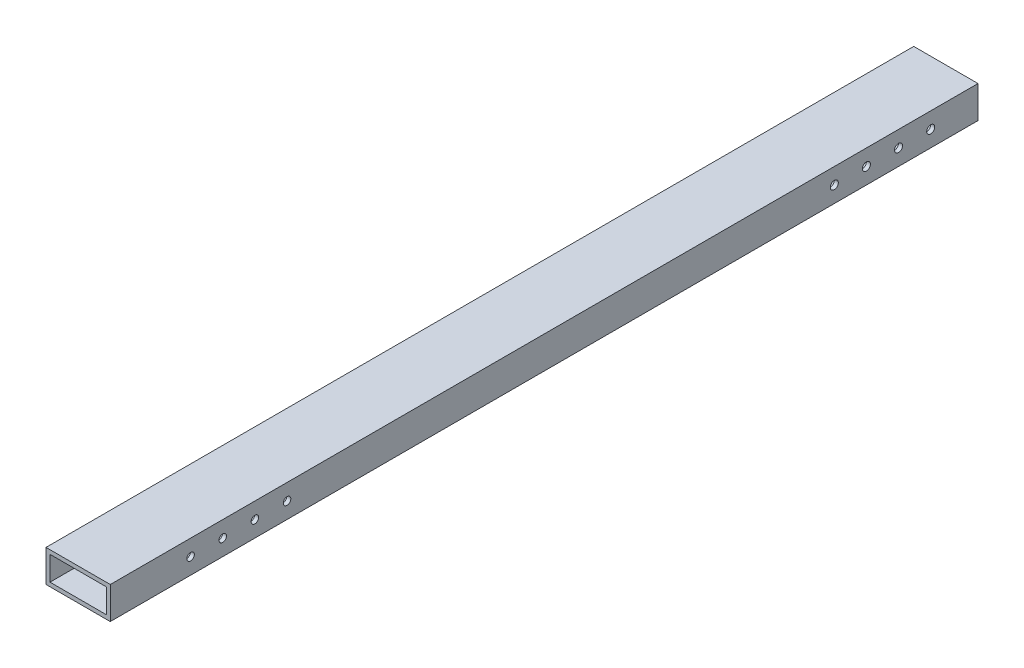
SolidWorks part; units mm, degrees
ref_plane "Front Plane" through (0, 0, 0) normal (0, 0, 1) x (1, 0, 0)
ref_plane "Top Plane" through (0, 0, 0) normal (0, 1, 0) x (1, 0, 0)
ref_plane "Right Plane" through (0, 0, 0) normal (1, 0, 0) x (0, 0, -1)
sketch "Sketch1" plane through (0, 0, 0) normal (0, 0, 1) x (1, 0, 0)
  line L0 (-22.225, 9.525) -> (22.225, 9.525)
  line L2 (-25.4, 12.7) -> (25.4, 12.7)
  line L3 (-25.4, 12.7) -> (-25.4, -12.7)
  line L4 (-25.4, -12.7) -> (25.4, -12.7)
  line L5 (25.4, 12.7) -> (25.4, -12.7)
  line L10 (22.225, 9.525) -> (22.225, -9.525)
  line L11 (-22.225, -9.525) -> (22.225, -9.525)
  line L12 (-22.225, 9.525) -> (-22.225, -9.525)
  point P12 (0, 12.7)
  point P14 (25.4, 0)
  dimension "Wall Thickness" = 3.175
  dimension "Outside Width" = 50.8
  dimension "Outside Height" = 25.4
  dimension "Inside Height" = 19.05
  dimension "Inside Width" = 44.45
sketch "Sketch2" plane through (0, 0, 0) normal (1, 0, 0) x (0, 0, -1)
  line L0 (342.9, 0) -> (-342.9, 0)
  point P4 (0, 0)
  point P7 (-342.9, 0)
  point P10 (342.9, 0)
  dimension "Length" = 685.8
sketch "Sketch3" plane through (0, 0, 0) normal (0, 0, 1) x (1, 0, 0)
  line L21 (25.4, 12.7) -> (-25.4, 12.7)
  line L22 (25.4, -12.7) -> (25.4, 12.7)
  line L23 (-25.4, -12.7) -> (25.4, -12.7)
  line L24 (-25.4, 12.7) -> (-25.4, -12.7)
  line L25 (25.4, 12.7) -> (-25.4, 12.7)
  line L26 (25.4, -12.7) -> (25.4, 12.7)
  line L27 (-25.4, -12.7) -> (25.4, -12.7)
  line L28 (-25.4, 12.7) -> (-25.4, -12.7)
  line L29 (22.225, 9.525) -> (-22.225, 9.525)
  line L30 (22.225, -9.525) -> (22.225, 9.525)
  line L31 (-22.225, -9.525) -> (22.225, -9.525)
  line L32 (-22.225, 9.525) -> (-22.225, -9.525)
  line L33 (22.225, 9.525) -> (-22.225, 9.525)
  line L34 (22.225, -9.525) -> (22.225, 9.525)
  line L35 (-22.225, -9.525) -> (22.225, -9.525)
  line L36 (-22.225, 9.525) -> (-22.225, -9.525)
  dimension "D1" = 0
  dimension "D2" = 0
extrude "Boss-Extrude1" add sketch "Sketch3" along normal up to vertex (342.9 mm away) and the other way up to vertex (342.9 mm away) up to point (0, 0, 342.9) other way up to point (0, 0, -342.9)
sketch "Drawing Reference" plane through (0, 0, 0) normal (1, 0, 0) x (0, 0, -1)
  line L0 (-342.9, 0) -> (342.9, 0) construction
  line L1 (0, -12.7) -> (0, 12.7) construction
  line L2 (-342.9, -12.7) -> (342.9, -12.7) construction
  line L5 (-342.9, 12.7) -> (342.9, 12.7) construction
  point P7 (-306.324, 0)
  point P8 (306.324, 0)
  dimension "D1" = 36.576
sketch "Sketch5" plane through (25.4, 0, 0) normal (1, 0, 0) x (0, 0, -1)
  line L0 (-342.9, 0) -> (-279.4, 0)
  line L1 (-342.9, -12.7) -> (-342.9, 12.7) construction
  line L2 (-279.4, 0) -> (-254, 0)
  line L3 (-254, 0) -> (-228.6, 0)
  line L4 (-228.6, 0) -> (-203.2, 0)
hole_wizard "A (0.234) Diameter Hole1" positions "Sketch6" profile "Sketch7" hole size "A" standard "ANSI Inch" end condition through all
sketch "Sketch6" plane through (25.4, 0, 0) normal (1, 0, 0) x (0, 0, -1)
  point P0 (-279.4, 0)
  point P3 (-254, 0)
  point P6 (-228.6, 0)
  point P9 (-203.2, 0)
sketch "Sketch7" plane through (25.4, 0, 279.4) normal (0, 1, 0) x (0, 0, -1)
  line L0 (0, 0) -> (0, 50.8)
  line L1 (0, 50.8) -> (2.9718, 50.8)
  line L2 (2.9718, 50.8) -> (2.9718, 0)
  line L5 (2.9718, 0) -> (0, 0)
  line L11 (0, -6.35) -> (0, 107.95) construction
  dimension "Thru Hole Dia." = 5.9436
  dimension "Thru Hole Depth" = 50.8
sketch "Sketch8" plane through (25.4, 0, 0) normal (1, 0, 0) x (0, 0, -1)
  line L0 (342.9, 0) -> (305.5118, 0)
  line L1 (342.9, -12.7) -> (342.9, 12.7) construction
  line L2 (305.5118, 0) -> (280.1118, 0)
  line L3 (280.1118, 0) -> (254.7118, 0)
  line L4 (254.7118, 0) -> (229.3118, 0)
hole_wizard "1/4 (0.25) Diameter Hole2" positions "Sketch9" profile "Sketch11" hole size "1/4" standard "ANSI Inch" end condition through all
sketch "Sketch9" plane through (25.4, 0, 0) normal (1, 0, 0) x (0, 0, -1)
  point P0 (305.5118, 0)
  point P3 (280.1118, 0)
  point P6 (254.7118, 0)
  point P9 (229.3118, 0)
sketch "Sketch11" plane through (25.4, 0, -305.5118) normal (0, 1, 0) x (0, 0, -1)
  line L0 (0, 0) -> (0, 50.8)
  line L1 (0, 50.8) -> (3.175, 50.8)
  line L2 (3.175, 50.8) -> (3.175, 0)
  line L5 (3.175, 0) -> (0, 0)
  line L11 (0, -6.35) -> (0, 107.95) construction
  dimension "Thru Hole Dia." = 6.35
  dimension "Thru Hole Depth" = 50.8
equation "\"D1@Drawing Reference\"=\"Outside Width@Sketch1\" * 0.72"
